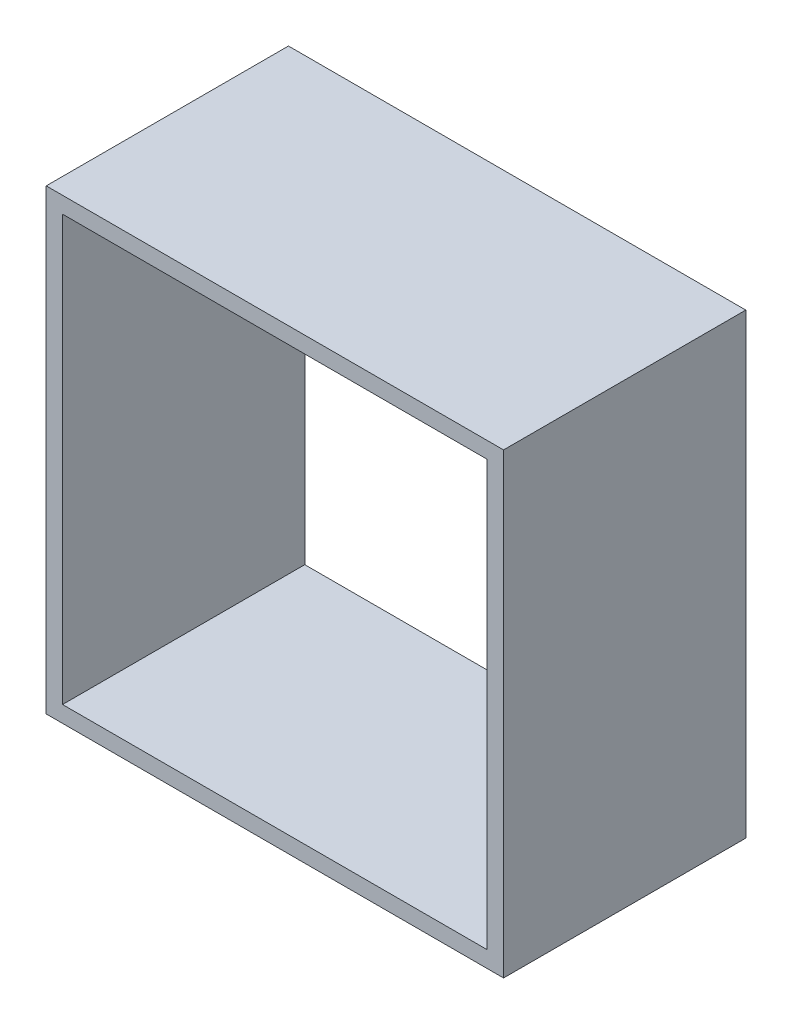
SolidWorks part; units mm, degrees
ref_plane "Plan de face" through (0, 0, 0) normal (0, 0, 1) x (1, 0, 0)
ref_plane "Plan de dessus" through (0, 0, 0) normal (0, 1, 0) x (1, 0, 0)
ref_plane "Plan de droite" through (0, 0, 0) normal (1, 0, 0) x (0, 0, -1)
sketch "Esquisse1" plane through (0, 0, 0) normal (0, 0, 1) x (1, 0, 0)
sketch "Esquisse2" plane through (0, 0, 0) normal (0, 0, 1) x (1, 0, 0)
  line L1 (-14, -14) -> (14, -14)
  line L2 (-14, -14) -> (-14, 14)
  line L3 (-14, 14) -> (14, 14)
  line L4 (14, -14) -> (14, 14)
  line L5 (-14, -14) -> (14, 14) construction
  line L6 (-14, 14) -> (14, -14) construction
  point P4 (0, 0)
extrude "Boss.-Extru.1" add sketch "Esquisse2" along normal blind 14.83
sketch "Esquisse3" plane through (0, 0, 14.83) normal (0, 0, 1) x (1, 0, 0)
  line L1 (-13, -13) -> (13, -13)
  line L2 (-13, -13) -> (-13, 13)
  line L3 (-13, 13) -> (13, 13)
  line L4 (13, -13) -> (13, 13)
  line L5 (-13, -13) -> (13, 13) construction
  line L6 (-13, 13) -> (13, -13) construction
  point P4 (0, 0)
extrude "Enlèv. mat.-Extru.1" cut sketch "Esquisse3" against normal blind 50
